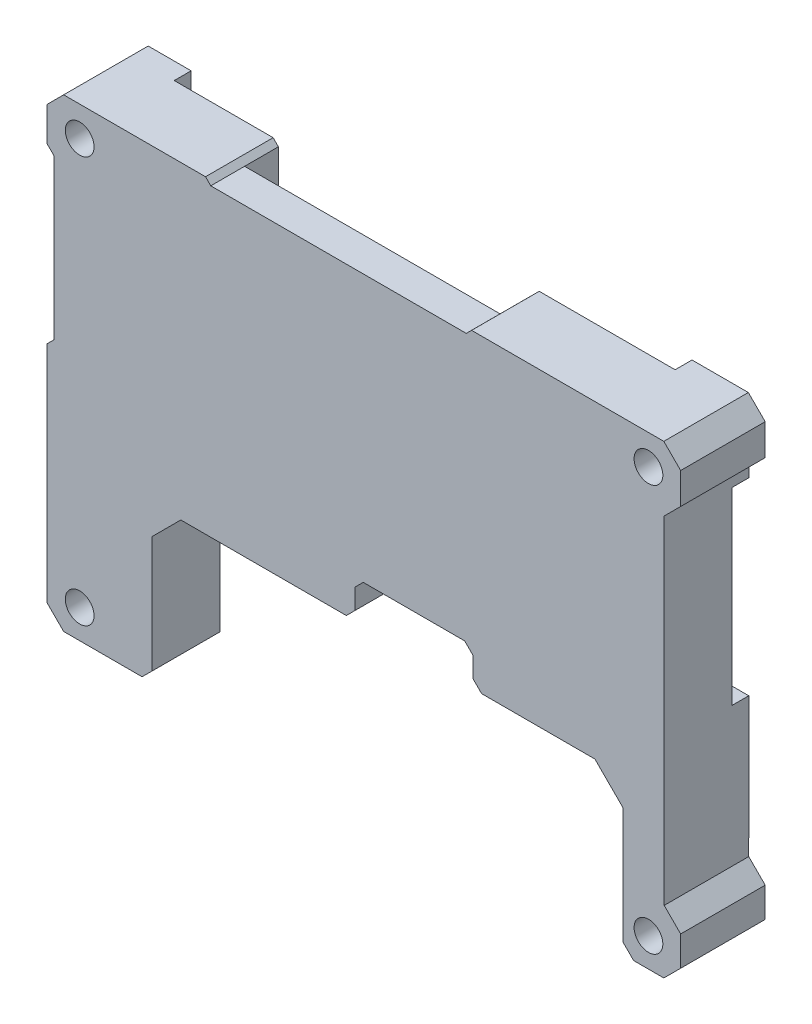
SolidWorks part; units mm, degrees
ref_plane "前视基准面" through (0, 0, 0) normal (0, 0, 1) x (1, 0, 0)
ref_plane "上视基准面" through (0, 0, 0) normal (0, 1, 0) x (1, 0, 0)
ref_plane "右视基准面" through (0, 0, 0) normal (1, 0, 0) x (0, 0, -1)
other "Configuration Table"
sketch "草图1" plane through (0, 0, 0) normal (0, 0, 1) x (1, 0, 0)
  line L1 (0, 0) -> (85, 0)
  line L2 (0, 0) -> (0, 65)
  line L3 (0, 65) -> (85, 65)
  line L4 (85, 0) -> (85, 65)
  dimension "D1" = 65
  dimension "D2" = 85
extrude "凸台-拉伸1" add sketch "草图1" along normal blind 10
sketch "草图2" plane through (0, 0, 0) normal (0, 0, -1) x (-1, 0, 0)
  circle A0 centre (-76.1669, 56.4425) radius 1.7
  circle A1 centre (-8.8888, 56.4425) radius 1.7
  circle A2 centre (-76.1669, 8.4151) radius 1.7
  circle A3 centre (-8.8888, 8.4151) radius 1.7
extrude "切除-拉伸1" cut sketch "草图2" against normal up to next
sketch "草图3" plane through (0, 0, 0) normal (0, 0, -1) x (-1, 0, 0)
  line L28 (-85, 0) -> (-85, 65) construction
  line L29 (-85, 65) -> (0, 65)
  line L30 (-85, 65) -> (-85, 0)
  line L31 (-85, 0) -> (0, 0)
  line L32 (0, 65) -> (0, 0)
  line L56 (-5, 33.4629) -> (-5.8713, 34.3342)
  line L57 (-5, 6.9926) -> (-5, 33.4629)
  line L58 (-6.9926, 5) -> (-5, 6.9926)
  line L59 (-16.2697, 5) -> (-6.9926, 5)
  line L60 (-17.4616, 6.1866) -> (-16.2697, 5)
  line L61 (-31.7436, 6.1829) -> (-17.4616, 6.1866)
  line L62 (-32.9265, 5) -> (-31.7436, 6.1829)
  line L63 (-58.7727, 5) -> (-32.9265, 5)
  line L64 (-60.0435, 6.2655) -> (-58.7727, 5)
  line L65 (-73.1524, 6.2618) -> (-60.0435, 6.2655)
  line L66 (-74.4142, 5) -> (-73.1524, 6.2618)
  line L67 (-77.9822, 5) -> (-74.4142, 5)
  line L68 (-79.9747, 6.9926) -> (-77.9822, 5)
  line L69 (-79.9747, 10.5083) -> (-79.9747, 6.9926)
  line L70 (-78.0283, 12.46) -> (-79.9747, 10.5083)
  line L71 (-78.032, 52.3531) -> (-78.0283, 12.46)
  line L72 (-79.9747, 54.2958) -> (-78.032, 52.3531)
  line L73 (-79.9747, 57.9821) -> (-79.9747, 54.2958)
  line L74 (-77.9822, 59.9747) -> (-79.9747, 57.9821)
  line L75 (-55.2451, 59.9747) -> (-77.9822, 59.9747)
  line L76 (-54.6148, 59.3497) -> (-55.2451, 59.9747)
  line L77 (-24.3949, 59.3534) -> (-54.6148, 59.3497)
  line L78 (-23.7736, 59.9747) -> (-24.3949, 59.3534)
  line L79 (-6.9926, 59.9747) -> (-23.7736, 59.9747)
  line L80 (-5, 57.9821) -> (-6.9926, 59.9747)
  line L81 (-5, 54.0174) -> (-5, 57.9821)
  line L82 (-5.875, 53.1371) -> (-5, 54.0174)
  line L83 (-5.8713, 34.3342) -> (-5.875, 53.1371)
extrude "切除-拉伸2" cut sketch "草图3" against normal up to next
sketch "草图4" plane through (0, 0, 0) normal (0, 0, -1) x (-1, 0, 0)
  line L0 (-73.1524, 6.2618) -> (-73.1524, 20.0323)
  line L1 (-73.1524, 20.0323) -> (-69.8316, 23.3532)
  line L2 (-69.8316, 23.3532) -> (-46.788, 23.3532)
  line L3 (-46.788, 23.3532) -> (-20.8513, 23.3532)
  line L4 (-20.8513, 23.3532) -> (-17.4616, 19.9634)
  line L5 (-17.4616, 19.9634) -> (-17.4616, 6.1866)
  line L6 (-31.7436, 6.1829) -> (-17.4616, 6.1866) construction
  line L7 (-17.4616, 6.1866) -> (-17.4616, 0.194)
  line L8 (-17.4616, 0.194) -> (-73.1524, 0.194)
  line L9 (-73.1524, 0.194) -> (-73.1524, 6.2618)
  line L10 (-73.1524, 6.2618) -> (-60.0435, 6.2655) construction
  dimension "D1" = 135
  dimension "D2" = 135
extrude "切除-拉伸4" cut sketch "草图4" against normal up to next
sketch "草图5" plane through (0, 0, 0) normal (0, 0, -1) x (-1, 0, 0)
  line L0 (-24.3949, 59.3534) -> (-24.3949, 53.9064)
  line L1 (-24.3949, 53.9064) -> (-25.5261, 52.7749)
  line L2 (-25.5261, 52.7749) -> (-53.4826, 52.7749)
  line L3 (-53.4826, 52.7749) -> (-54.6142, 53.9061)
  line L4 (-54.6142, 53.9061) -> (-54.6148, 59.3497)
  line L5 (-24.3949, 59.3534) -> (-54.6148, 59.3497) construction
  line L6 (-23.7736, 59.9747) -> (-24.3949, 59.3534) construction
  line L7 (-24.3949, 59.3534) -> (-54.6148, 59.3497)
  dimension "D1" = 135
  dimension "D2" = 134.993
  dimension "D3" = 1.6
  dimension "D4" = 1.6
extrude "切除-拉伸7" cut sketch "草图5" against normal blind 6
sketch "草图6" plane through (0, 0, 0) normal (0, 0, -1) x (-1, 0, 0)
  line L14 (-5.8713, 34.3342) -> (-9.8713, 34.3342)
  line L15 (-5.8713, 34.3342) -> (-5.8713, 50.3342)
  line L16 (-5.8713, 50.3342) -> (-9.8713, 50.3342)
  line L17 (-9.8713, 34.3342) -> (-9.8713, 50.3342)
  dimension "D1" = 4
  dimension "D2" = 16
extrude "切除-拉伸8" cut sketch "草图6" against normal blind 6
sketch "草图7" plane through (0, 0, 0) normal (0, 0, -1) x (-1, 0, 0)
  line L0 (-76.4321, 51.2623) -> (-74.4321, 51.2623)
  line L1 (-74.4321, 51.2623) -> (-71.3195, 54.3749)
  line L2 (-71.3195, 54.3749) -> (-71.3195, 58.3749)
  line L3 (-71.3195, 58.3749) -> (-71.3195, 59.9747)
  line L4 (-76.4321, 51.2623) -> (-78.0319, 51.2623)
  line L5 (-78.0298, 28.9377) -> (-75.0298, 28.9377)
  line L6 (-75.0298, 28.9377) -> (-75.0298, 13.9377)
  line L7 (-72.9158, 11.8236) -> (-75.0298, 13.9377)
  line L8 (-12.072, 58.334) -> (-12.072, 59.9747)
  line L11 (-12.072, 58.334) -> (-12.072, 55.334)
  line L12 (-12.072, 55.334) -> (-9.875, 53.1371)
  line L13 (-9.875, 53.1371) -> (-5.875, 53.1371)
  line L14 (-6.5998, 12.014) -> (-10.5998, 12.014)
  line L15 (-10.5998, 12.014) -> (-12.014, 10.5998)
  line L16 (-12.014, 10.5998) -> (-12.014, 5)
  line L17 (-6.5998, 12.014) -> (-5, 12.014)
  line L18 (-72.9158, 11.8236) -> (-73.1524, 12.0603)
  line L37 (-5.8713, 34.3342) -> (-9.8713, 34.3342)
  line L38 (-5.8713, 34.3342) -> (-9.8713, 34.3342)
  line L39 (-9.8713, 34.3342) -> (-9.8713, 50.3342)
  line L40 (-9.8713, 34.3342) -> (-9.8713, 50.3342)
  line L41 (-9.8713, 50.3342) -> (-5.8745, 50.3342)
  line L42 (-5.8745, 50.3342) -> (-5.875, 53.1371)
  line L43 (-5.875, 53.1371) -> (-5, 54.0174)
  line L44 (-5, 54.0174) -> (-5, 57.9821)
  line L45 (-5, 57.9821) -> (-6.9926, 59.9747)
  line L46 (-6.9926, 59.9747) -> (-23.7736, 59.9747)
  line L47 (-23.7736, 59.9747) -> (-24.3949, 59.3534)
  line L48 (-24.3949, 59.3534) -> (-24.3949, 53.9064)
  line L49 (-24.3949, 53.9064) -> (-25.5261, 52.7749)
  line L50 (-25.5261, 52.7749) -> (-53.4826, 52.7749)
  line L51 (-53.4826, 52.7749) -> (-54.6142, 53.9061)
  line L52 (-54.6142, 53.9061) -> (-54.6148, 59.3497)
  line L53 (-54.6148, 59.3497) -> (-55.2451, 59.9747)
  line L54 (-55.2451, 59.9747) -> (-77.9822, 59.9747)
  line L55 (-77.9822, 59.9747) -> (-79.9747, 57.9821)
  line L56 (-79.9747, 57.9821) -> (-79.9747, 54.2958)
  line L57 (-79.9747, 54.2958) -> (-78.032, 52.3531)
  line L58 (-78.032, 52.3531) -> (-78.0283, 12.46)
  line L59 (-78.0283, 12.46) -> (-79.9747, 10.5083)
  line L60 (-79.9747, 10.5083) -> (-79.9747, 6.9926)
  line L61 (-79.9747, 6.9926) -> (-77.9822, 5)
  line L62 (-77.9822, 5) -> (-74.4142, 5)
  line L63 (-74.4142, 5) -> (-73.1524, 6.2618)
  line L64 (-73.1524, 6.2618) -> (-73.1524, 20.0323)
  line L65 (-73.1524, 20.0323) -> (-69.8316, 23.3532)
  line L66 (-69.8316, 23.3532) -> (-20.8513, 23.3532)
  line L67 (-20.8513, 23.3532) -> (-17.4616, 19.9634)
  line L68 (-17.4616, 19.9634) -> (-17.4616, 6.1866)
  line L69 (-17.4616, 6.1866) -> (-16.2697, 5)
  line L70 (-16.2697, 5) -> (-6.9926, 5)
  line L71 (-6.9926, 5) -> (-5, 6.9926)
  line L72 (-5, 6.9926) -> (-5, 33.4629)
  line L73 (-5, 33.4629) -> (-5.8713, 34.3342)
  line L79 (-5.8745, 50.3342) -> (-5.875, 53.1371)
  line L80 (-5.875, 53.1371) -> (-5, 54.0174)
  line L81 (-5, 54.0174) -> (-5, 57.9821)
  line L82 (-5, 57.9821) -> (-6.9926, 59.9747)
  line L83 (-6.9926, 59.9747) -> (-23.7736, 59.9747)
  line L84 (-23.7736, 59.9747) -> (-24.3949, 59.3534)
  line L85 (-24.3949, 59.3534) -> (-24.3949, 53.9064)
  line L86 (-24.3949, 53.9064) -> (-25.5261, 52.7749)
  line L87 (-25.5261, 52.7749) -> (-53.4826, 52.7749)
  line L88 (-53.4826, 52.7749) -> (-54.6142, 53.9061)
  line L89 (-54.6142, 53.9061) -> (-54.6148, 59.3497)
  line L90 (-54.6148, 59.3497) -> (-55.2451, 59.9747)
  line L91 (-55.2451, 59.9747) -> (-77.9822, 59.9747)
  line L92 (-77.9822, 59.9747) -> (-79.9747, 57.9821)
  line L93 (-79.9747, 57.9821) -> (-79.9747, 54.2958)
  line L94 (-79.9747, 54.2958) -> (-78.032, 52.3531)
  line L95 (-78.032, 52.3531) -> (-78.0283, 12.46)
  line L96 (-78.0283, 12.46) -> (-79.9747, 10.5083)
  line L97 (-79.9747, 10.5083) -> (-79.9747, 6.9926)
  line L98 (-79.9747, 6.9926) -> (-77.9822, 5)
  line L99 (-77.9822, 5) -> (-74.4142, 5)
  line L100 (-74.4142, 5) -> (-73.1524, 6.2618)
  line L101 (-73.1524, 6.2618) -> (-73.1524, 20.0323)
  line L102 (-73.1524, 20.0323) -> (-69.8316, 23.3532)
  line L103 (-69.8316, 23.3532) -> (-20.8513, 23.3532)
  line L104 (-20.8513, 23.3532) -> (-17.4616, 19.9634)
  line L105 (-17.4616, 19.9634) -> (-17.4616, 6.1866)
  line L106 (-17.4616, 6.1866) -> (-16.2697, 5)
  line L107 (-16.2697, 5) -> (-6.9926, 5)
  line L108 (-6.9926, 5) -> (-5, 6.9926)
  line L109 (-5, 6.9926) -> (-5, 33.4629)
  line L110 (-5, 33.4629) -> (-5.8713, 34.3342)
  line L126 (-9.8713, 50.3342) -> (-5.8745, 50.3342)
  dimension "D2" = 90
  dimension "D3" = 15
  dimension "D4" = 135
  dimension "D5" = 4
  dimension "D6" = 3
  dimension "D7" = 2.1969
  dimension "D8" = 45
  dimension "D9" = 3
  dimension "D1" = 0
extrude "切除-拉伸11" cut sketch "草图7" against normal blind 2
sketch "草图15" plane through (0, 0, 10) normal (0, 0, 1) x (1, 0, 0)
  line L0 (69.8316, 23.3532) -> (20.8513, 23.3532) construction
  line L1 (41.4288, 23.3532) -> (55.4288, 23.3532)
  line L2 (41.4288, 23.3532) -> (41.4288, 27.7532)
  line L3 (41.4288, 27.7532) -> (55.4288, 27.7532)
  line L4 (55.4288, 23.3532) -> (55.4288, 27.7532)
  dimension "D1" = 14
  dimension "D2" = 4.4
extrude "切除-拉伸13" cut sketch "草图15" against normal up to surface (8 mm away) up to face at (35.5266, 37.5618, 2)
chamfer "倒角1" distance 1 angle 45 4 edges at (41.4288, 23.3532, 6) (41.4288, 27.7532, 6) (55.4288, 27.7532, 6) (55.4288, 23.3532, 6)
